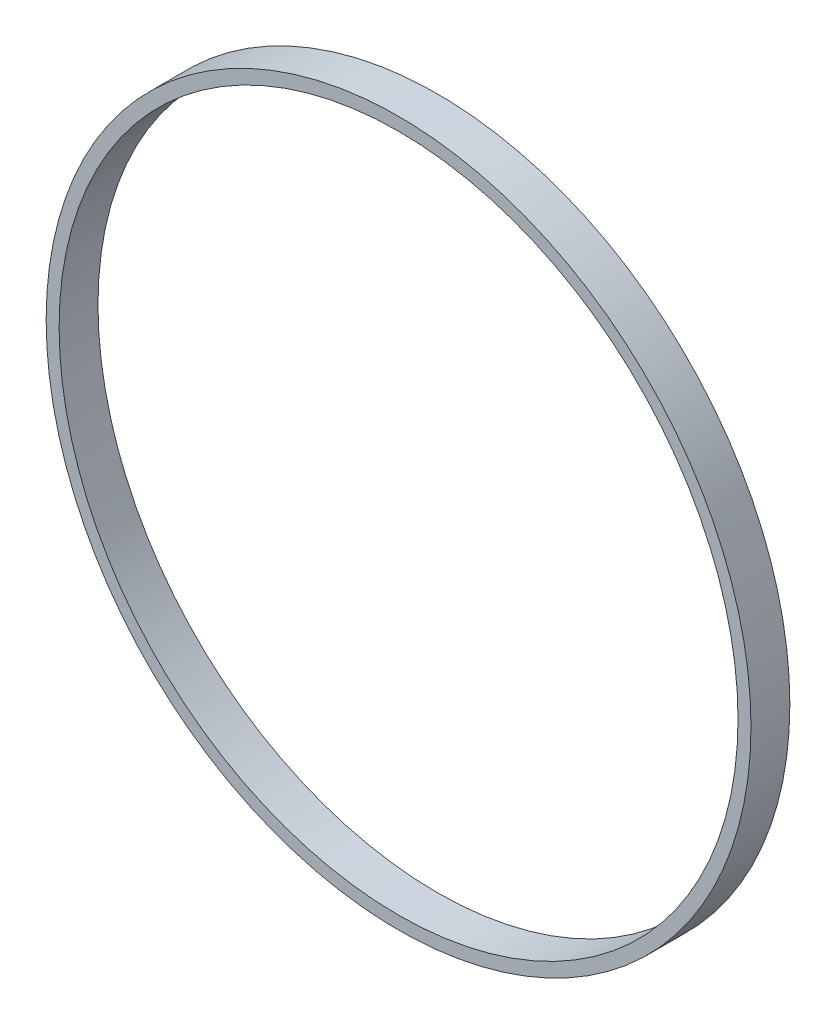
SolidWorks part; units mm, degrees
ref_plane "Front Plane" through (0, 0, 0) normal (0, 0, 1) x (1, 0, 0)
ref_plane "Top Plane" through (0, 0, 0) normal (0, 1, 0) x (1, 0, 0)
ref_plane "Right Plane" through (0, 0, 0) normal (1, 0, 0) x (0, 0, -1)
sketch "Sketch2" plane through (0, 0, 0) normal (0, 0, 1) x (1, 0, 0)
  circle A0 centre (0, 0) radius 86.36
  circle A1 centre (0, 0) radius 83.185
  dimension "D1" = 172.72
  dimension "D2" = 3.175
extrude "Boss-Extrude1" add sketch "Sketch2" along normal blind 9.525
